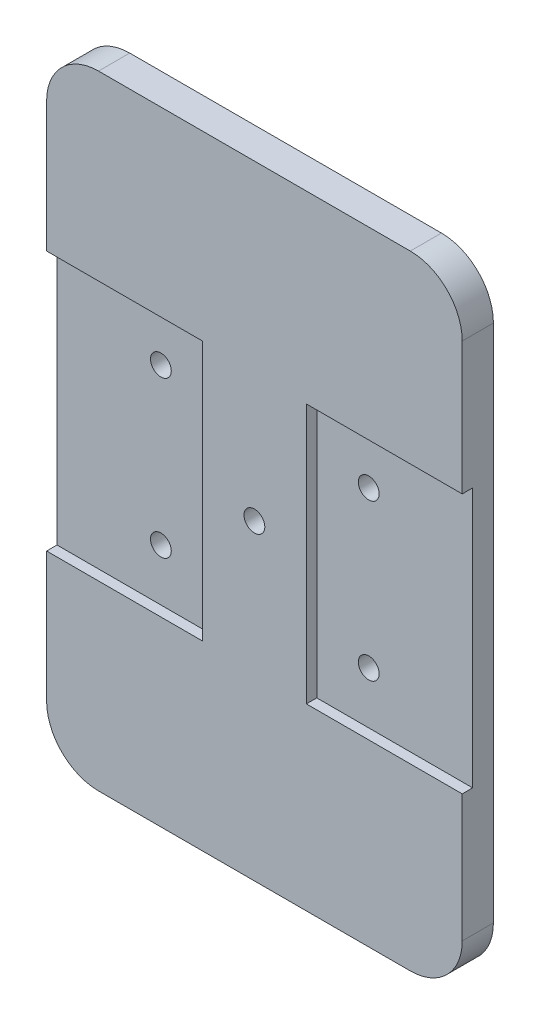
SolidWorks part; units mm, degrees
ref_plane "Front Plane" through (0, 0, 0) normal (0, 0, 1) x (1, 0, 0)
ref_plane "Top Plane" through (0, 0, 0) normal (0, 1, 0) x (1, 0, 0)
ref_plane "Right Plane" through (0, 0, 0) normal (1, 0, 0) x (0, 0, -1)
sketch "Sketch1" plane through (0, 0, 0) normal (0, 0, 1) x (1, 0, 0)
  line L1 (-65.9851, 26.8064) -> (-25.9851, 26.8064)
  line L2 (-65.9851, 26.8064) -> (-65.9851, -33.1936)
  line L3 (-65.9851, -33.1936) -> (-25.9851, -33.1936)
  line L4 (-25.9851, 26.8064) -> (-25.9851, -33.1936)
  dimension "D1" = 40
  dimension "D2" = 60
extrude "Boss-Extrude4" add sketch "Sketch1" against normal blind 3 contours L2 L3 L4 L1
sketch "Sketch5" plane through (0, 0, 0) normal (0, 0, 1) x (1, 0, 0)
  line L0 (-65.9851, 26.8064) -> (-65.9851, -33.1936) construction
  line L1 (-65.9851, 9.3064) -> (-50.9851, 9.3064)
  line L2 (-65.9851, 9.3064) -> (-65.9851, -15.6936)
  line L3 (-65.9851, -15.6936) -> (-50.9851, -15.6936)
  line L4 (-50.9851, 9.3064) -> (-50.9851, -15.6936)
  line L5 (-65.9851, 26.8064) -> (-25.9851, 26.8064) construction
  dimension "D1" = 15
  dimension "D2" = 25
  dimension "D3" = 17.5
extrude "Cut-Extrude2" cut sketch "Sketch5" against normal blind 1 contours L2 L1 L4 L3
sketch "Sketch7" plane through (0, 0, -1) normal (0, 0, 1) x (1, 0, 0)
  line L0 (-65.9851, 9.3064) -> (-50.9851, 9.3064) construction
  line L1 (-50.9851, 9.3064) -> (-50.9851, -15.6936) construction
  circle A0 centre (-55.9851, 4.3064) radius 1
  dimension "D1" = 2
  dimension "D2" = 5
  dimension "D3" = 5
extrude "Cut-Extrude3" cut sketch "Sketch7" against normal blind 2
sketch "Sketch8" plane through (0, 0, -1) normal (0, 0, 1) x (1, 0, 0)
  line L0 (-50.9851, 9.3064) -> (-50.9851, -15.6936) construction
  line L1 (-65.9851, -15.6936) -> (-50.9851, -15.6936) construction
  circle A0 centre (-55.9851, -10.6936) radius 1
  dimension "D1" = 5
  dimension "D3" = 2
  dimension "D2" = 5
extrude "Cut-Extrude4" cut sketch "Sketch8" against normal blind 2
fillet "Fillet1" radius 5 4 edges at (-25.9851, 26.8064, -1.5) (-25.9851, -33.1936, -1.5) (-65.9851, -33.1936, -1.5) (-65.9851, 26.8064, -1.5)
sketch "Sketch12" plane through (0, 0, -3) normal (0, 0, -1) x (-1, 0, 0)
  line L0 (65.9851, 21.8064) -> (65.9851, -28.1936) construction
  line L1 (60.9851, 26.8064) -> (30.9851, 26.8064) construction
  circle A0 centre (45.9851, -3.1936) radius 1
  dimension "D1" = 2
  dimension "D2" = 20
  dimension "D3" = 30
extrude "Cut-Extrude6" cut sketch "Sketch12" against normal blind 12 contours A0
sketch "Sketch13" plane through (0, 0, 0) normal (0, 0, 1) x (1, 0, 0)
  line L0 (-25.9851, 21.8064) -> (-25.9851, -28.1936) construction
  line L1 (-25.9851, 9.0634) -> (-40.9851, 9.0634)
  line L2 (-25.9851, 9.0634) -> (-25.9851, -15.9366)
  line L3 (-25.9851, -15.9366) -> (-40.9851, -15.9366)
  line L4 (-40.9851, 9.0634) -> (-40.9851, -15.9366)
  dimension "D1" = 15
  dimension "D2" = 25
extrude "Cut-Extrude7" cut sketch "Sketch13" against normal blind 1 contours L2 L1 L4 L3
sketch "Sketch14" plane through (0, 0, -1) normal (0, 0, 1) x (1, 0, 0)
  line L0 (-25.9851, 9.0634) -> (-25.9851, -15.9366) construction
  line L1 (-25.9851, 9.0634) -> (-40.9851, 9.0634) construction
  line L2 (-25.9851, -15.9366) -> (-40.9851, -15.9366) construction
  circle A0 centre (-35.9851, 4.0634) radius 1
  circle A1 centre (-35.9851, -10.9366) radius 1
  dimension "D1" = 10
  dimension "D2" = 10
  dimension "D3" = 5
  dimension "D4" = 5
extrude "Cut-Extrude8" cut sketch "Sketch14" against normal blind 7
